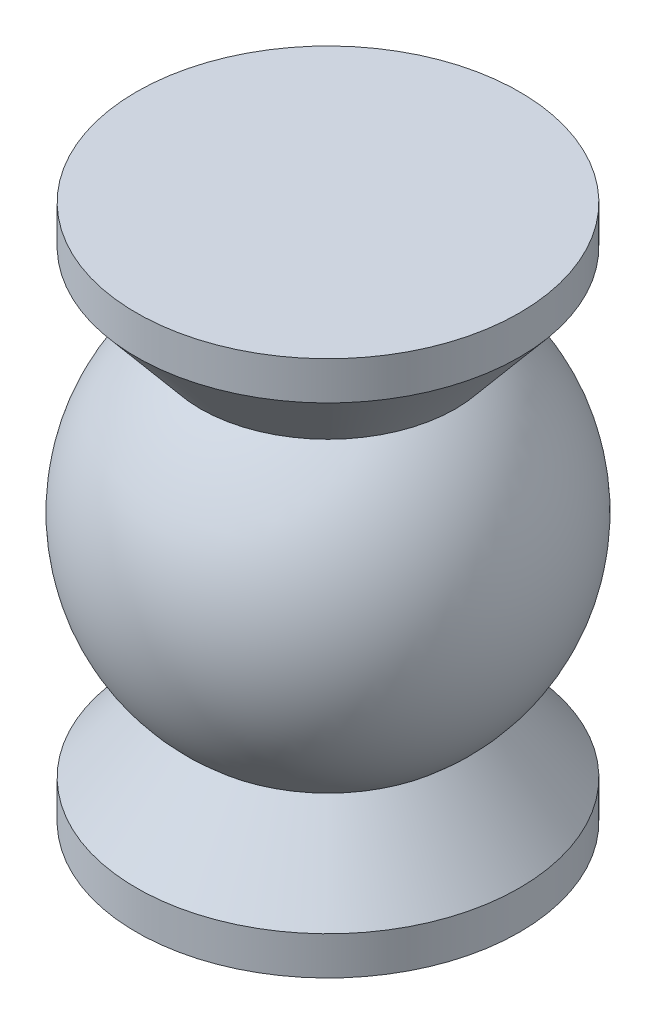
SolidWorks part; units mm, degrees
ref_plane "前视基准面" through (0, 0, 0) normal (0, 0, 1) x (1, 0, 0)
ref_plane "上视基准面" through (0, 0, 0) normal (0, 1, 0) x (1, 0, 0)
ref_plane "右视基准面" through (0, 0, 0) normal (1, 0, 0) x (0, 0, -1)
other "Configuration Table"
sketch "草图1" plane through (0, 0, 0) normal (0, 0, 1) x (1, 0, 0)
  line L0 (-34.3639, 0) -> (30.6818, 0) construction
  line L1 (0, 0) -> (-25, 0)
  line L2 (-25, 0) -> (-25, -5)
  line L5 (-25, -65) -> (-25, -70)
  line L6 (-25, -70) -> (0, -70)
  line L7 (0, 0) -> (0, -70) construction
  line L8 (-25, -5) -> (-16.6667, -15)
  line L9 (-25, -65) -> (-16.6667, -55)
  line L10 (0, 0) -> (0, -70)
  arc A1 (-16.6667, -15) -> (-16.6667, -55) centre (0, -35) ccw
  dimension "D1" = 25
  dimension "D2" = 5
  dimension "D3" = 5
  dimension "D4" = 40
  dimension "D7" = 70
revolve "旋转1" add sketch "草图1" angle 360 about L10
